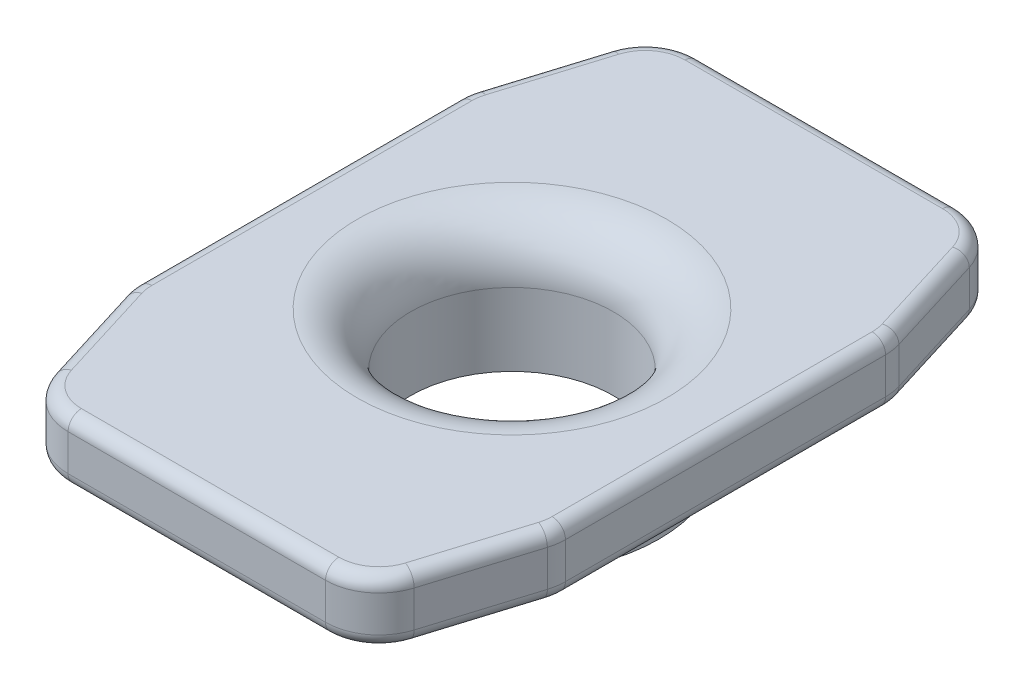
SolidWorks part; units mm, degrees
ref_plane "Front Plane" through (0, 0, 0) normal (0, 0, 1) x (1, 0, 0)
ref_plane "Top Plane" through (0, 0, 0) normal (0, 1, 0) x (1, 0, 0)
ref_plane "Right Plane" through (0, 0, 0) normal (1, 0, 0) x (0, 0, -1)
sketch "Sketch1" plane through (0, 0, 0) normal (0, 1, 0) x (1, 0, 0)
  line L0 (-4, 7.5) -> (-5.08, 4)
  line L1 (5.08, 7.5) -> (-5.08, 7.5)
  line L2 (5.08, 7.5) -> (5.08, -7.5)
  line L3 (5.08, -7.5) -> (-5.08, -7.5)
  line L4 (-5.08, 7.5) -> (-5.08, -7.5)
  line L5 (5.08, 7.5) -> (-5.08, -7.5) construction
  line L6 (5.08, -7.5) -> (-5.08, 7.5) construction
  line L7 (0, 7.5) -> (0, -7.5) construction
  line L8 (4, 7.5) -> (5.08, 4)
  line L9 (-5.08, 0) -> (5.08, 0) construction
  line L10 (4, -7.5) -> (5.08, -4)
  line L11 (-4, -7.5) -> (-5.08, -4)
  circle A0 centre (0, 0) radius 2.413
  point P0 (0, 0)
  dimension "D5" = 4.826
  dimension "D1" = 10.16
  dimension "D2" = 15
  dimension "D3" = 4
  dimension "D4" = 4
extrude "Boss-Extrude1" add sketch "Sketch1" along normal blind 1.5 contours L11 L3 L10 L2 L8 L1 L0 L4 A0
sketch "Sketch2" plane through (0, 0, 0) normal (0, -1, 0) x (1, 0, 0)
  circle A0 centre (0, 0) radius 3.5
  circle A1 centre (0, 0) radius 2.413 construction
  circle A2 centre (0, 0) radius 2.413
  circle M1 centre (0, 0) radius 2.413
  dimension "D1" = 7
extrude "Boss-Extrude2" add sketch "Sketch2" along normal offset from surface (1.5 mm away) 3 contours A0 M1 up to face at (0, 1.5, 2.413)
fillet "Fillet1" radius 1.27 9 edges at (0, 1.5, 2.413) (4, 0.75, 7.5) (-4, 0.75, 7.5) (-5.08, 0.75, 4) (-5.08, 0.75, -4) (-4, 0.75, -7.5) (4, 0.75, -7.5) (5.08, 0.75, -4) (5.08, 0.75, 4)
fillet "Fillet2" radius 0.3175 33 edges at (5.0658, 0, -3.9979) (4.6499, 0, -5.3937) (3.8169, 0, -7.2519) (0, 0, -7.5) (-3.8169, 0, -7.2519) (-4.6499, 0, -5.3937) (-5.0658, 0, -3.9979) (-5.08, 0, 0) (-5.0658, 0, 3.9979) (-4.6499, 0, 5.3937) (-3.8169, 0, 7.2519) (0, 0, 7.5) (3.8169, 0, 7.2519) (4.6499, 0, 5.3937) (5.0658, 0, 3.9979) (3.8169, 1.5, 7.2519) (0, 1.5, 7.5) (-3.8169, 1.5, 7.2519) (-4.6499, 1.5, 5.3937) (-5.0658, 1.5, 3.9979) (-5.08, 1.5, 0) (-5.0658, 1.5, -3.9979) (-4.6499, 1.5, -5.3937) (-3.8169, 1.5, -7.2519) (0, 1.5, -7.5) (3.8169, 1.5, -7.2519) (4.6499, 1.5, -5.3937) (5.0658, 1.5, -3.9979) (5.08, 1.5, 0) (5.0658, 1.5, 3.9979) (5.08, 0, 0) (4.6499, 1.5, 5.3937) (0, 0, 3.5)
